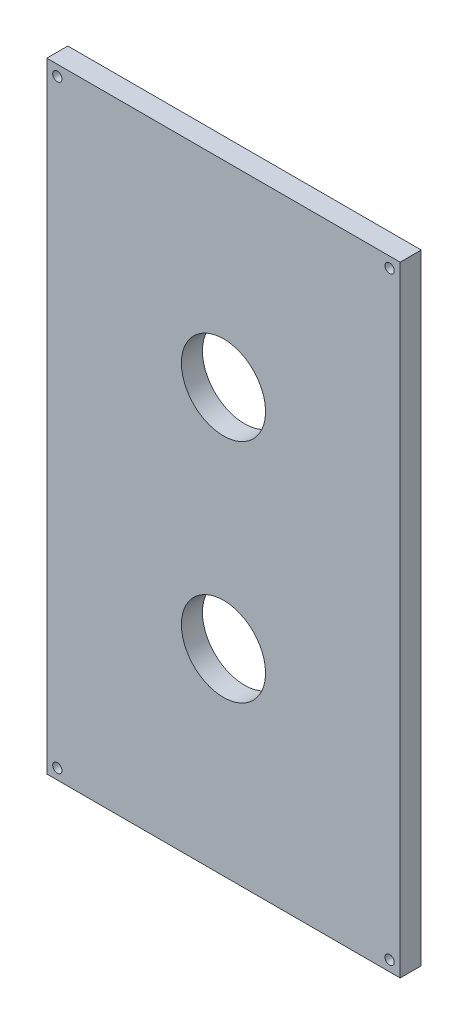
SolidWorks part; units mm, degrees
ref_plane "Front Plane" through (0, 0, 0) normal (0, 0, 1) x (1, 0, 0)
ref_plane "Top Plane" through (0, 0, 0) normal (0, 1, 0) x (1, 0, 0)
ref_plane "Right Plane" through (0, 0, 0) normal (1, 0, 0) x (0, 0, -1)
sketch "Sketch1" plane through (0, 0, 0) normal (0, 0, 1) x (1, 0, 0)
  line L0 (0, 0) -> (-83.98, 0)
  line L1 (-83.98, 0) -> (-83.98, 147.35)
  line L2 (-83.98, 147.35) -> (0, 147.35)
  line L3 (0, 147.35) -> (0, 0)
  dimension "D1" = 83.98
  dimension "D2" = 147.35
extrude "platform_thickness" add sketch "Sketch1" along normal blind 5
sketch "Sketch2" plane through (0, 0, 0) normal (0, 0, -1) x (-1, 0, 0)
  line L0 (41.99, 100.585) -> (41.99, 46.765) construction
  line L1 (41.99, 46.765) -> (41.99, 0) construction
  line L2 (83.98, 0) -> (0, 0) construction
  line L3 (41.99, 100.585) -> (41.99, 147.35) construction
  line L4 (0, 147.35) -> (83.98, 147.35) construction
  line L5 (41.99, 100.585) -> (83.98, 100.585) construction
  line L6 (83.98, 147.35) -> (83.98, 0) construction
  line L7 (41.99, 100.585) -> (0, 100.585) construction
  line L8 (0, 0) -> (0, 147.35) construction
  circle A0 centre (41.99, 100.585) radius 10
  circle A1 centre (41.99, 46.765) radius 10
  dimension "D1" = 20
  dimension "D2" = 53.82
extrude "io_hole_1" cut sketch "Sketch2" against normal through all
sketch "Sketch3" plane through (0, 0, 0) normal (0, 0, -1) x (-1, 0, 0)
  line L0 (2.5, 144.85) -> (81.48, 144.85) construction
  line L1 (81.48, 144.85) -> (81.48, 2.5) construction
  line L2 (81.48, 2.5) -> (2.5, 2.5) construction
  line L3 (2.5, 2.5) -> (2.5, 144.85) construction
  line L4 (2.5, 144.85) -> (0, 144.85) construction
  line L5 (0, 0) -> (0, 147.35) construction
  line L6 (81.48, 144.85) -> (83.98, 144.85) construction
  line L7 (83.98, 147.35) -> (83.98, 0) construction
  line L8 (81.48, 2.5) -> (83.98, 2.5) construction
  line L9 (2.5, 2.5) -> (0, 2.5) construction
  line L10 (2.5, 2.5) -> (2.5, 0) construction
  line L11 (83.98, 0) -> (0, 0) construction
  line L12 (81.48, 2.5) -> (81.48, 0) construction
  line L13 (2.5, 144.85) -> (2.5, 147.35) construction
  line L14 (0, 147.35) -> (83.98, 147.35) construction
  line L15 (81.48, 144.85) -> (81.48, 147.35) construction
  circle A0 centre (2.5, 144.85) radius 1.1
  circle A1 centre (81.48, 144.85) radius 1.1
  circle A2 centre (81.48, 2.5) radius 1.1
  circle A3 centre (2.5, 2.5) radius 1.1
  dimension "D1" = 2.2
  dimension "D2" = 2.5
  dimension "D3" = 2.5
extrude "mounting_holes" cut sketch "Sketch3" against normal through all
